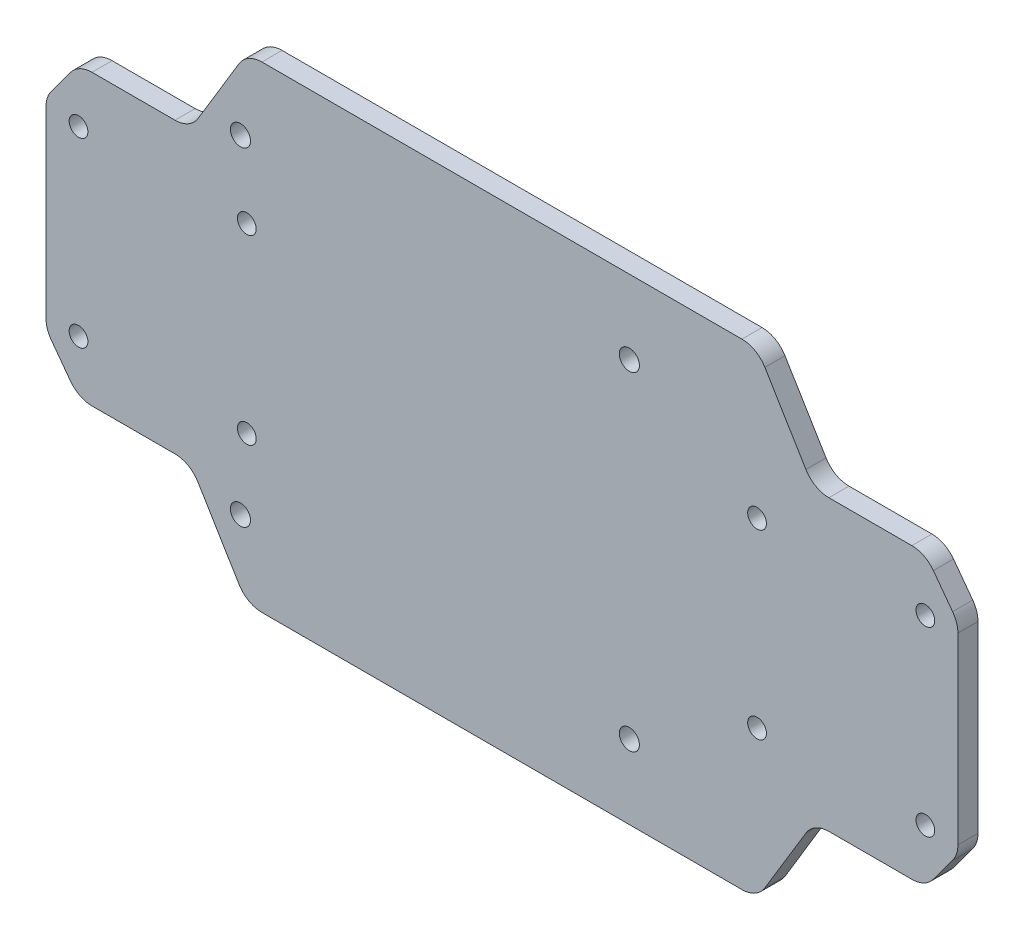
SolidWorks part; units mm, degrees
ref_plane "Front Plane" through (0, 0, 0) normal (0, 0, 1) x (1, 0, 0)
ref_plane "Top Plane" through (0, 0, 0) normal (0, 1, 0) x (1, 0, 0)
ref_plane "Right Plane" through (0, 0, 0) normal (1, 0, 0) x (0, 0, -1)
sketch "Sketch1" plane through (0, 0, 0) normal (0, 0, 1) x (1, 0, 0)
  line L0 (0, 0) -> (38.05, 0) construction
  line L1 (38.05, 0) -> (38.05, -13.55) construction
  line L2 (38.05, -13.55) -> (63.15, -13.55) construction
  line L3 (38.05, 0) -> (63.15, 0) construction
  line L4 (63.15, 0) -> (63.15, -13.55) construction
  line L5 (0, 0) -> (0, 16.3161) construction
  line L6 (63.15, 13.55) -> (63.15, -13.55) construction
  line L7 (63.15, 0) -> (68, 0) construction
  line L8 (0, 0) -> (-39, 0) construction
  line L9 (-39, 0) -> (-39, 24.5) construction
  line L10 (-39, 24.5) -> (19, 24.5) construction
  line L11 (68, -13.6803) -> (68, 13.6803)
  line L12 (0, 0) -> (0, -36.5) construction
  line L13 (0, -36.5) -> (-46.5, -36.5) construction
  line L14 (63.15, 13.55) -> (63.15, 21.55) construction
  line L15 (67.2147, 16.0606) -> (64.3493, 19.9303)
  line L16 (61.1346, 21.55) -> (48.7578, 21.55)
  line L17 (38.05, 13.55) -> (38.05, 35.55) construction
  line L18 (45.3333, 23.483) -> (39.2167, 33.617)
  line L19 (0, 16.3161) -> (0, 35.55) construction
  line L20 (35.7922, 35.55) -> (-35.7922, 35.55)
  line L21 (67.2147, -16.0606) -> (64.3493, -19.9303)
  line L22 (61.1346, -21.55) -> (48.7578, -21.55)
  line L23 (45.3333, -23.483) -> (39.2167, -33.617)
  line L24 (35.7922, -35.55) -> (-35.7922, -35.55)
  line L25 (-45.3333, -23.483) -> (-39.2167, -33.617)
  line L26 (-61.1346, -21.55) -> (-48.7578, -21.55)
  line L27 (-67.2147, -16.0606) -> (-64.3493, -19.9303)
  line L28 (-68, -13.6803) -> (-68, 13.6803)
  line L29 (-67.2147, 16.0606) -> (-64.3493, 19.9303)
  line L30 (-61.1346, 21.55) -> (-48.7578, 21.55)
  line L31 (-45.3333, 23.483) -> (-39.2167, 33.617)
  circle A0 centre (38.05, -13.55) radius 1.4
  circle A1 centre (63.15, -13.55) radius 1.4
  circle A2 centre (63.15, 13.55) radius 1.4
  circle A3 centre (38.05, 13.55) radius 1.4
  circle A4 centre (-38.05, -13.55) radius 1.4
  circle A5 centre (-63.15, -13.55) radius 1.4
  circle A6 centre (-63.15, 13.55) radius 1.4
  circle A7 centre (-38.05, 13.55) radius 1.4
  circle A8 centre (-39, 24.5) radius 1.5
  circle A9 centre (19, 24.5) radius 1.5
  circle A10 centre (19, -24.5) radius 1.5
  circle A11 centre (-39, -24.5) radius 1.5
  arc A16 (68, 13.6803) -> (67.2147, 16.0606) centre (64, 13.6803) ccw
  arc A17 (64.3493, 19.9303) -> (61.1346, 21.55) centre (61.1346, 17.55) ccw
  arc A18 (48.7578, 21.55) -> (45.3333, 23.483) centre (48.7578, 25.55) cw
  arc A19 (39.2167, 33.617) -> (35.7922, 35.55) centre (35.7922, 31.55) ccw
  arc A20 (68, -13.6803) -> (67.2147, -16.0606) centre (64, -13.6803) cw
  arc A21 (64.3493, -19.9303) -> (61.1346, -21.55) centre (61.1346, -17.55) cw
  arc A22 (48.7578, -21.55) -> (45.3333, -23.483) centre (48.7578, -25.55) ccw
  arc A23 (39.2167, -33.617) -> (35.7922, -35.55) centre (35.7922, -31.55) cw
  arc A24 (-39.2167, -33.617) -> (-35.7922, -35.55) centre (-35.7922, -31.55) ccw
  arc A25 (-48.7578, -21.55) -> (-45.3333, -23.483) centre (-48.7578, -25.55) cw
  arc A26 (-64.3493, -19.9303) -> (-61.1346, -21.55) centre (-61.1346, -17.55) ccw
  arc A27 (-68, -13.6803) -> (-67.2147, -16.0606) centre (-64, -13.6803) ccw
  arc A28 (-68, 13.6803) -> (-67.2147, 16.0606) centre (-64, 13.6803) cw
  arc A29 (-64.3493, 19.9303) -> (-61.1346, 21.55) centre (-61.1346, 17.55) cw
  arc A30 (-48.7578, 21.55) -> (-45.3333, 23.483) centre (-48.7578, 25.55) ccw
  arc A31 (-39.2167, 33.617) -> (-35.7922, 35.55) centre (-35.7922, 31.55) cw
  point P47 (68, 15)
  point P70 (0, -35.55)
  dimension "D4" = 2.8
  dimension "D5" = 2.8
  dimension "D10" = 3
  dimension "D11" = 3
  dimension "D18" = 4
  dimension "D1" = 38.05
  dimension "D2" = 13.55
  dimension "D3" = 25.1
  dimension "D6" = 4.85
  dimension "D7" = 39
  dimension "D8" = 24.5
  dimension "D9" = 58
  dimension "D12" = 15
  dimension "D13" = 36.5
  dimension "D14" = 46.5
  dimension "D16" = 8
  dimension "D17" = 22
extrude "Boss-Extrude1" add sketch "Sketch1" along normal blind 3
